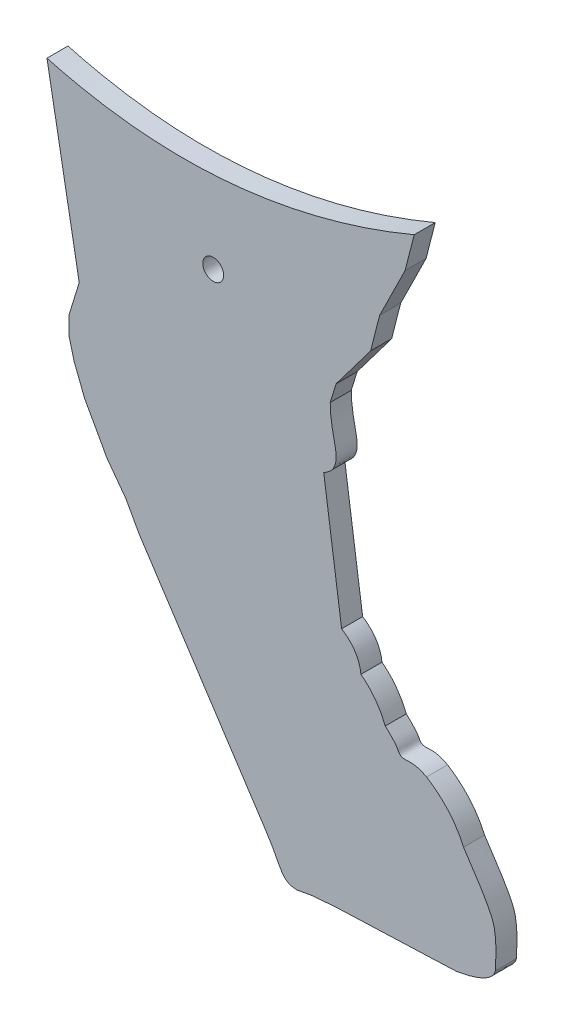
SolidWorks part; units mm, degrees
ref_plane "Front Plane" through (0, 0, 0) normal (0, 0, 1) x (1, 0, 0)
ref_plane "Top Plane" through (0, 0, 0) normal (0, 1, 0) x (1, 0, 0)
ref_plane "Right Plane" through (0, 0, 0) normal (1, 0, 0) x (0, 0, -1)
sketch "Sketch1" plane through (0, 0, 0) normal (0, 0, 1) x (1, 0, 0)
  line L0 (134.6667, 500.5) -> (673.3333, 500.5) construction
  line L1 (95.0151, 73.0396) -> (93.4424, 67.9472)
  line L2 (93.4424, 67.9472) -> (93.4424, 65.401)
  line L3 (93.4424, 65.401) -> (94.2288, 62.4055)
  line L4 (94.2288, 62.4055) -> (95.8389, 58.2866)
  line L5 (95.8389, 58.2866) -> (97.8609, 54.617)
  line L6 (97.8609, 54.617) -> (99.1877, 52.209)
  line L7 (99.1877, 52.209) -> (102.0546, 48.3264)
  line L8 (102.0546, 48.3264) -> (104.0449, 44.7143)
  line L9 (104.0449, 44.7143) -> (123.0328, 15.7186)
  line L10 (127.9651, 10.0937) -> (130.0459, 10.4701)
  line L11 (130.0459, 10.4701) -> (133.7876, 10.7747)
  line L12 (133.7876, 10.7747) -> (151.9742, 11.4708)
  line L14 (133.7876, 79.1971) -> (132.8975, 76.3148)
  line L15 (131.9168, 66.6741) -> (134.5134, 48.3264)
  line L16 (134.5134, 48.3264) -> (134.6174, 47.5914)
  line L18 (133.7876, 79.1971) -> (138.9956, 86.1016)
  line L19 (138.9956, 86.1016) -> (140.3613, 91.4507)
  line L20 (140.3613, 91.4507) -> (143.1224, 97.0274)
  line L21 (143.1224, 97.0274) -> (144.2001, 99.204)
  line L22 (144.2001, 99.204) -> (145.5707, 104.5722)
  line L23 (95.0151, 73.0396) -> (92.4998, 86.9439)
  line L24 (92.4998, 86.9439) -> (90.1483, 99.9431)
  circle A0 centre (115.2395, 84.8849) radius 1.5748
  spline S0 degree 3 poles (123.0328, 15.7186) (123.7143, 14.7232) (125.0279, 12.417) (126.1313, 9.9933) (127.9651, 10.0937) knots 0 0 0 0 0.482545 1 1 1 1
  spline S1 degree 3 poles (141.2086, 38.1802) (142.0578, 37.3364) (142.6965, 36.8317) (143.8648, 34.5581) (144.8079, 36.0573) (147.4373, 34.6374) knots 0 0 0 0 0.387994 0.411005 1 1 1 1
  spline S2 degree 2 poles (147.4373, 34.6374) (151.3117, 32.1818) (153.0172, 28.2463) knots 0 0 0 1 1 1
  spline S3 degree 3 poles (153.0172, 28.2463) (155.0535, 25.0973) (156.1686, 23.6544) (158.1463, 19.3121) (157.9006, 15.9258) (157.8294, 14.5022) knots 0 0 0 0 0.545638 0.593854 1 1 1 1
  spline S4 degree 3 poles (157.8294, 14.5022) (157.371, 12.4487) (153.4132, 11.7402) (151.9742, 11.4708) knots 0 0 0 0 1 1 1 1
  spline S5 degree 2 poles (90.1483, 99.9431) (116.963, 92.5784) (145.5707, 104.5722) knots 0 0 0 1 1 1
  spline S6 degree 3 poles (132.8975, 76.3148) (132.9159, 73.1979) (134.3834, 69.9755) (133.3842, 67.4244) (131.9168, 66.6741) knots 0 0 0 0 0.575324 1 1 1 1
  spline S7 degree 2 poles (134.6174, 47.5914) (137.2297, 45.9166) (137.5361, 43.0923) knots 0 0 0 1 1 1
  spline S8 degree 2 poles (137.5361, 43.0923) (139.9841, 41.2453) (141.2086, 38.1802) knots 0 0 0 1 1 1
extrude "Boss-Extrude2" add sketch "Sketch1" along normal blind 3.175
